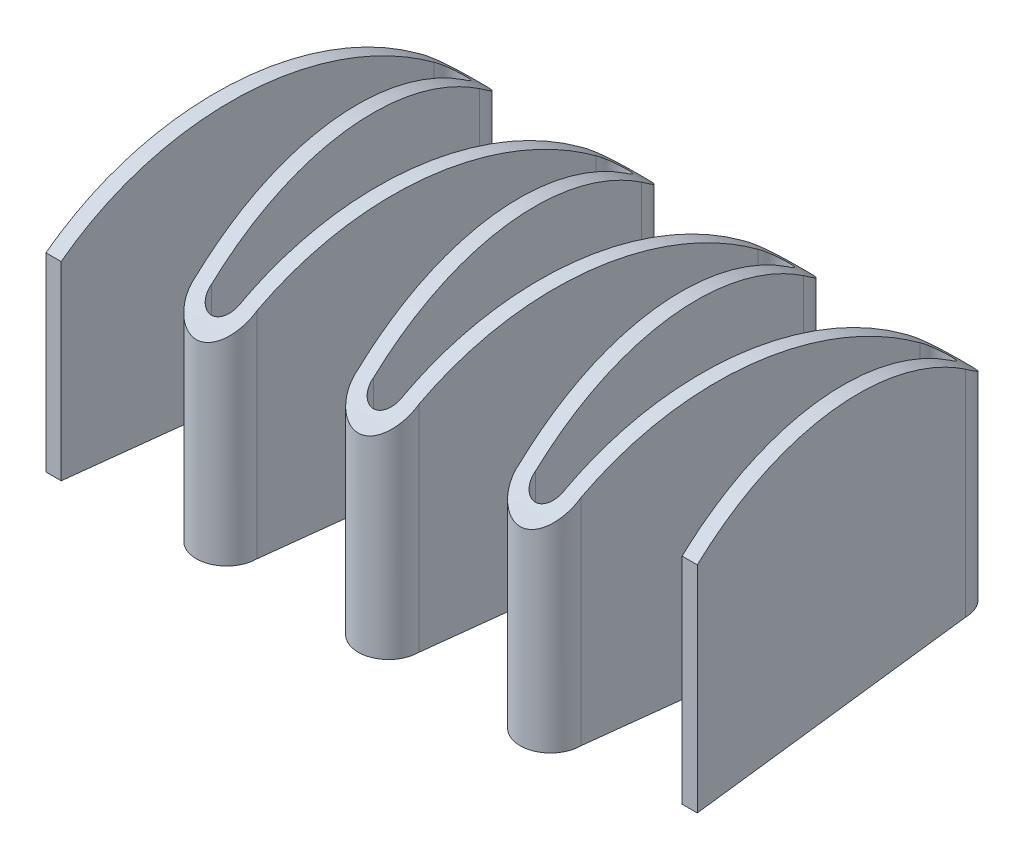
SolidWorks part; units mm, degrees
ref_plane "前视基准面" through (0, 0, 0) normal (0, 0, 1) x (1, 0, 0)
ref_plane "上视基准面" through (0, 0, 0) normal (0, 1, 0) x (1, 0, 0)
ref_plane "右视基准面" through (0, 0, 0) normal (1, 0, 0) x (0, 0, -1)
other "Configuration Table"
sketch "草图1" plane through (0, 0, 0) normal (0, 1, 0) x (1, 0, 0)
  line L0 (0, 0) -> (2.1472, 0) construction
  line L1 (0, 0) -> (0, 11.4287) construction
  line L11 (0.75, 15) -> (2.5, 0)
  line L30 (1.5, 15) -> (3.25, 0)
  line L31 (2.5, 0) -> (5.5, 0) construction
  line L32 (-2.675, -1.5) -> (-3.425, -1.5)
  line L33 (-1.5, 15) -> (1.5, 15) construction
  line L34 (-1.5, 15) -> (-3.425, -1.5)
  line L35 (-0.75, 15) -> (-2.675, -1.5)
  line L36 (6.5, 15) -> (4.75, 0)
  line L37 (7.25, 15) -> (5.5, 0)
  line L38 (8.75, 15) -> (10.5, 0)
  line L39 (9.5, 15) -> (11.25, 0)
  line L40 (14.5, 15) -> (12.75, 0)
  line L41 (15.25, 15) -> (13.5, 0)
  line L42 (16.75, 15) -> (18.5, 0)
  line L43 (17.5, 15) -> (19.25, 0)
  line L44 (22.5, 15) -> (20.75, 0)
  line L45 (23.25, 15) -> (21.5, 0)
  line L46 (24.75, 15) -> (26.5, 0)
  line L47 (25.5, 15) -> (27.25, 0)
  line L48 (26.5, 0) -> (27.25, 0)
  arc A20 (0.75, 15) -> (-0.75, 15) centre (0, 15) ccw
  arc A21 (1.5, 15) -> (-1.5, 15) centre (0, 15) ccw
  arc A22 (3.25, 0) -> (4.75, 0) centre (4, 0) ccw
  arc A23 (2.5, 0) -> (5.5, 0) centre (4, 0) ccw
  arc A24 (9.5, 15) -> (6.5, 15) centre (8, 15) ccw
  arc A25 (8.75, 15) -> (7.25, 15) centre (8, 15) ccw
  arc A26 (11.25, 0) -> (12.75, 0) centre (12, 0) ccw
  arc A27 (10.5, 0) -> (13.5, 0) centre (12, 0) ccw
  arc A28 (17.5, 15) -> (14.5, 15) centre (16, 15) ccw
  arc A29 (16.75, 15) -> (15.25, 15) centre (16, 15) ccw
  arc A30 (19.25, 0) -> (20.75, 0) centre (20, 0) ccw
  arc A31 (18.5, 0) -> (21.5, 0) centre (20, 0) ccw
  arc A32 (25.5, 15) -> (22.5, 15) centre (24, 15) ccw
  arc A33 (24.75, 15) -> (23.25, 15) centre (24, 15) ccw
  arc A36 (26.5, 0) -> (29.5, 0) centre (28, 0) ccw [skipped]
  arc A37 (27.25, 0) -> (28.75, 0) centre (28, 0) ccw [skipped]
  dimension "D1" = 1.5
  dimension "D2" = 3
  dimension "D5" = 15
  dimension "D6" = 4
  dimension "D3" = 3
  dimension "D4" = 1.5
  dimension "D7" = 4
extrude "凸台-拉伸2" add sketch "草图1" along normal blind 13
sketch "草图2" plane through (0, 0, 0) normal (1, 0, 0) x (0, 0, -1)
  line L3 (-1.5, 13) -> (16.5, 13)
  line L4 (-1.5, 13) -> (-1.5, 0) construction
  line L5 (0, 0) -> (15, 0) construction
  line L10 (-1.5, 9.3808) -> (16.5, 9.3808) construction
  line L11 (-1.5, 13) -> (-1.5, 0)
  line L13 (16.5, 0) -> (16.5, 13) construction
  line L14 (16.5, 0) -> (16.5, 13)
  arc A0 (-1.5, 9.3808) -> (16.5, 9.3808) centre (7.5, 0) cw
extrude "切除-拉伸1" cut sketch "草图2" along normal through all both and the other way through all
